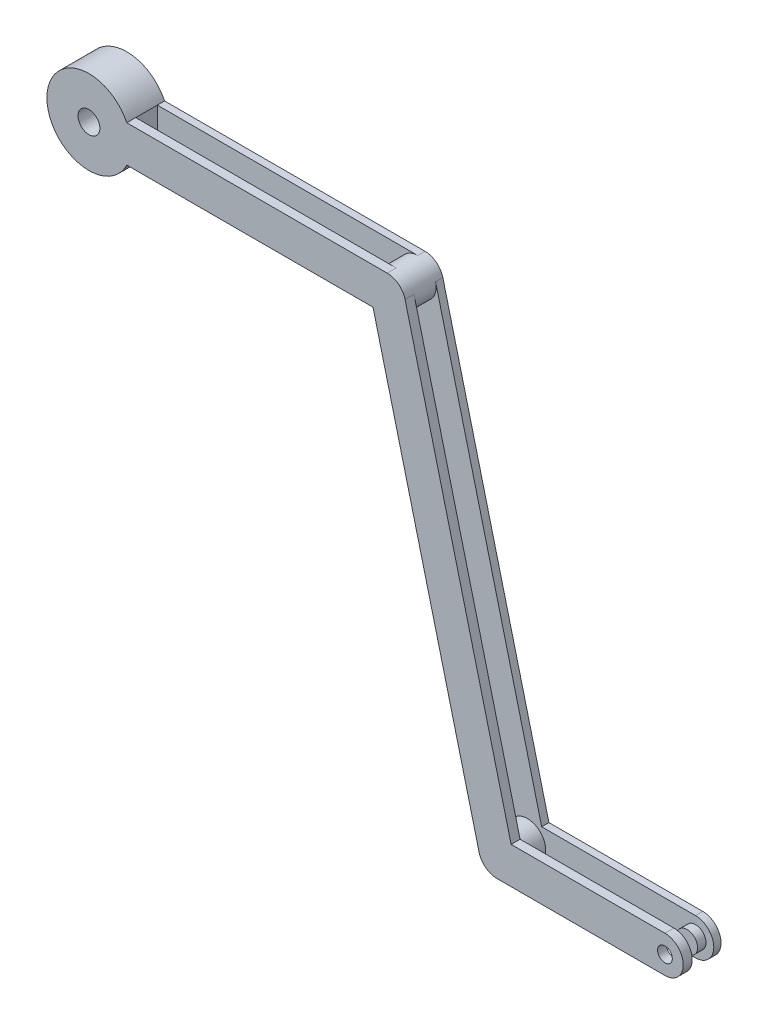
SolidWorks part; units mm, degrees
ref_plane "前视基准面" through (0, 0, 0) normal (0, 0, 1) x (1, 0, 0)
ref_plane "上视基准面" through (0, 0, 0) normal (0, 1, 0) x (1, 0, 0)
ref_plane "右视基准面" through (0, 0, 0) normal (1, 0, 0) x (0, 0, -1)
other "Configuration Table"
sketch "草图1" plane through (0, 0, 0) normal (0, 0, 1) x (1, 0, 0)
  line L0 (0, 0) -> (71, 0) construction
  line L1 (9, 4.3589) -> (71, 4.3589)
  line L2 (9, -4.3589) -> (67.6073, -4.3589)
  line L3 (72.4841, -5.8611) -> (97.081, -103) construction
  line L4 (75.2255, 1.07) -> (100.4737, -98.6411)
  line L5 (67.6073, -4.3589) -> (92.8554, -104.07)
  line L6 (97.081, -103) -> (137.081, -103) construction
  line L7 (100.4737, -98.6411) -> (137.081, -98.6411)
  line L8 (97.081, -107.3589) -> (137.081, -107.3589)
  line L9 (9, -4.3589) -> (9, 4.3589) construction
  arc A0 (9, 4.3589) -> (9, -4.3589) centre (0, 0) ccw
  arc A2 (75.2255, 1.07) -> (71, 4.3589) centre (71, 0) ccw
  arc A3 (75.2255, 1.07) -> (71, 4.3589) centre (71, 0) ccw
  arc A4 (92.8554, -104.07) -> (97.081, -107.3589) centre (97.081, -103) ccw
  arc A6 (137.081, -107.3589) -> (137.081, -98.6411) centre (137.081, -103) ccw
  arc A8 (92.8554, -104.07) -> (97.081, -107.3589) centre (97.081, -103) ccw
  point P4 (35.5, 0)
  point P11 (84.0405, -51.5)
  point P18 (117.081, -103)
  point P25 (0, 0)
  dimension "D1" = 20
  dimension "D2" = 9
  dimension "D3" = 71
  dimension "D4" = 103
  dimension "D5" = 40
extrude "凸台-拉伸1" add sketch "草图1" along normal blind 9 contours L8 A6 L7 L4 A2 L1 A0 L2 L5 A4
sketch "草图2" plane through (0, 0, 0) normal (0, 0, -1) x (-1, 0, 0)
  circle A0 centre (0, 0) radius 5.6
  dimension "D1" = 11.2
extrude "切除-拉伸1" cut sketch "草图2" against normal blind 4.6
sketch "草图3" plane through (0, 0, 9) normal (0, 0, 1) x (1, 0, 0)
  circle A0 centre (0, 0) radius 2.6
  dimension "D1" = 5.2
extrude "切除-拉伸2" cut sketch "草图3" against normal through all
sketch "草图5" plane through (0, 4.3589, 0) normal (0, 1, 0) x (1, 0, 0)
  line L0 (9, -1.7299) -> (9, -6.8696)
  line L1 (9, -9) -> (9, 0) construction
  line L2 (9, -6.8696) -> (141.4399, -6.8696)
  line L3 (141.4399, -9) -> (141.4399, 0) construction
  line L4 (141.4399, -6.8696) -> (141.4399, -1.7299)
  line L5 (141.4399, -1.7299) -> (9, -1.7299)
extrude "切除-拉伸3" cut sketch "草图5" against normal through all
sketch "草图6" plane through (0, 0, 9) normal (0, 0, 1) x (1, 0, 0)
  circle A0 centre (97.179, -102.8741) radius 4.4859
  circle A1 centre (71, 0) radius 4.3589
extrude "凸台-拉伸2" add sketch "草图6" against normal up to surface (7.2701 mm away) contours A1 up to face at (80.0764, -51.5, 1.7299)
sketch "草图7" plane through (0, 0, 9) normal (0, 0, 1) x (1, 0, 0)
  circle A0 centre (97.081, -103) radius 4.3589
extrude "凸台-拉伸3" add sketch "草图7" against normal up to surface (7.2701 mm away) up to face at (79.5409, -52.188, 1.7299)
sketch "草图8" plane through (0, 0, 1.7299) normal (0, 0, 1) x (1, 0, 0)
  circle A0 centre (137.081, -103) radius 2.5
  dimension "D1" = 5
extrude "凸台-拉伸4" add sketch "草图8" along normal blind 2
sketch "草图9" plane through (0, 0, 9) normal (0, 0, 1) x (1, 0, 0)
  circle A0 centre (137.081, -103) radius 1.75
  dimension "D1" = 3.5
extrude "切除-拉伸4" cut sketch "草图9" against normal up to next
